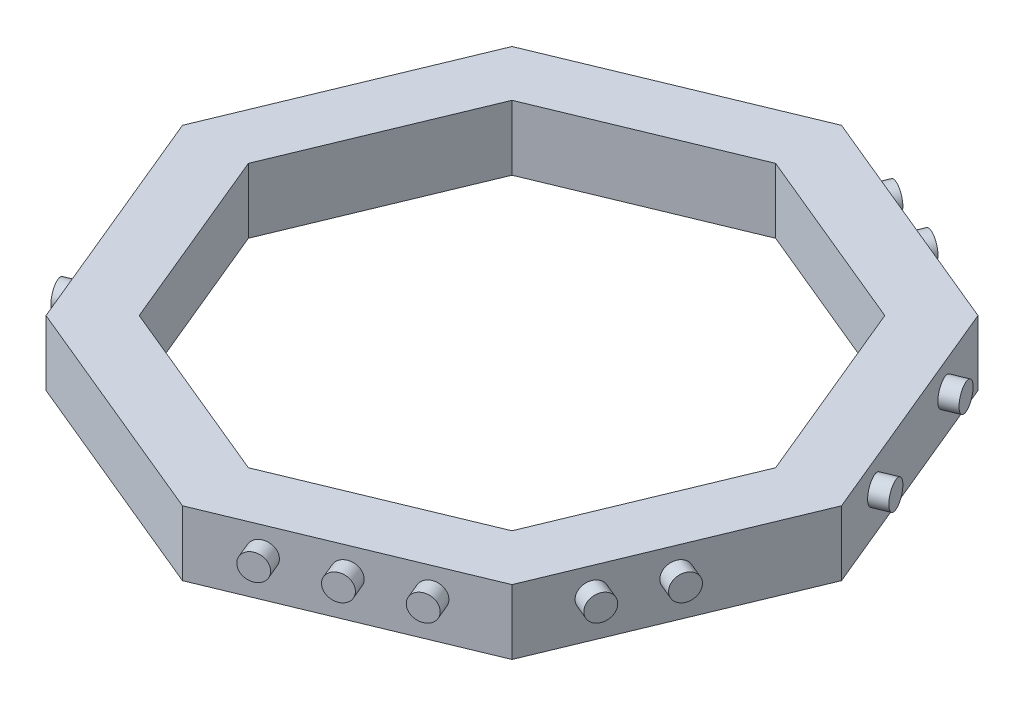
SolidWorks part; units mm, degrees
ref_plane "Front Plane" through (0, 0, 0) normal (0, 0, 1) x (1, 0, 0)
ref_plane "Top Plane" through (0, 0, 0) normal (0, 1, 0) x (1, 0, 0)
ref_plane "Right Plane" through (0, 0, 0) normal (1, 0, 0) x (0, 0, -1)
sketch "Sketch3" plane through (0, 0, 0) normal (0, 1, 0) x (1, 0, 0)
  line L1 (25.4, 0) -> (17.9605, 17.9605)
  line L2 (17.9605, 17.9605) -> (0, 25.4)
  line L3 (0, 25.4) -> (-17.9605, 17.9605)
  line L4 (-17.9605, 17.9605) -> (-25.4, 0)
  line L5 (-25.4, 0) -> (-17.9605, -17.9605)
  line L6 (-17.9605, -17.9605) -> (0, -25.4)
  line L7 (0, -25.4) -> (17.9605, -17.9605)
  line L8 (17.9605, -17.9605) -> (25.4, 0)
  circle A0 centre (0, 0) radius 23.4665 construction
  dimension "D1" = 25.4
extrude "Boss-Extrude1" add sketch "Sketch3" along normal blind 5
sketch "Sketch5" plane through (0, 5, 0) normal (0, 1, 0) x (1, 0, 0)
  line L1 (20.32, 0) -> (14.3684, 14.3684)
  line L2 (14.3684, 14.3684) -> (0, 20.32)
  line L3 (0, 20.32) -> (-14.3684, 14.3684)
  line L4 (-14.3684, 14.3684) -> (-20.32, 0)
  line L5 (-20.32, 0) -> (-14.3684, -14.3684)
  line L6 (-14.3684, -14.3684) -> (0, -20.32)
  line L7 (0, -20.32) -> (14.3684, -14.3684)
  line L8 (14.3684, -14.3684) -> (20.32, 0)
  circle A0 centre (0, 0) radius 18.7732 construction
  dimension "D1" = 20.32
extrude "Cut-Extrude1" cut sketch "Sketch5" against normal blind 5
sketch "Sketch6" plane through (8.9803, 0, 21.6803) normal (0.3827, 0, 0.9239) x (0.9239, 0, -0.3827)
  circle A0 centre (0, 3) radius 1
  circle A1 centre (-5, 3) radius 1
  circle A2 centre (5, 3) radius 1
sketch "Sketch7" plane through (-21.6803, 0, 8.9803) normal (-0.9239, 0, 0.3827) x (0.3827, 0, 0.9239)
  circle A0 centre (5, 3) radius 1
sketch "Sketch8" plane through (-21.6803, 0, -8.9803) normal (-0.9239, 0, -0.3827) x (-0.3827, 0, 0.9239)
  circle A0 centre (0, 3) radius 1
sketch "Sketch9" plane through (-8.9803, 0, -21.6803) normal (-0.3827, 0, -0.9239) x (-0.9239, 0, 0.3827)
  circle A0 centre (-5, 3) radius 1
sketch "Sketch10" plane through (8.9803, 0, -21.6803) normal (0.3827, 0, -0.9239) x (-0.9239, 0, -0.3827)
  circle A0 centre (0, 3) radius 1
  circle A1 centre (5, 3) radius 1
sketch "Sketch11" plane through (21.6803, 0, -8.9803) normal (0.9239, 0, -0.3827) x (-0.3827, 0, -0.9239)
  circle A0 centre (5, 3) radius 1
  circle A1 centre (-5, 3) radius 1
sketch "Sketch12" plane through (21.6803, 0, 8.9803) normal (0.9239, 0, 0.3827) x (0.3827, 0, -0.9239)
  circle A0 centre (0, 3) radius 1
  circle A1 centre (-5, 3) radius 1
extrude "Boss-Extrude5" add sketch "Sketch6" along normal blind 1.25 contours A2 | A1 | A0
extrude "Boss-Extrude6" add sketch "Sketch7" along normal blind 1.25 contours A0
extrude "Boss-Extrude7" add sketch "Sketch8" along normal blind 1.25 contours A0
extrude "Boss-Extrude8" add sketch "Sketch9" along normal blind 1.25 contours A0
extrude "Boss-Extrude12" add sketch "Sketch10" along normal blind 1.25 contours A0 | A1
extrude "Boss-Extrude13" add sketch "Sketch11" along normal blind 1.25 contours A1 | A0
extrude "Boss-Extrude14" add sketch "Sketch12" along normal blind 1.25 contours A1 | A0
